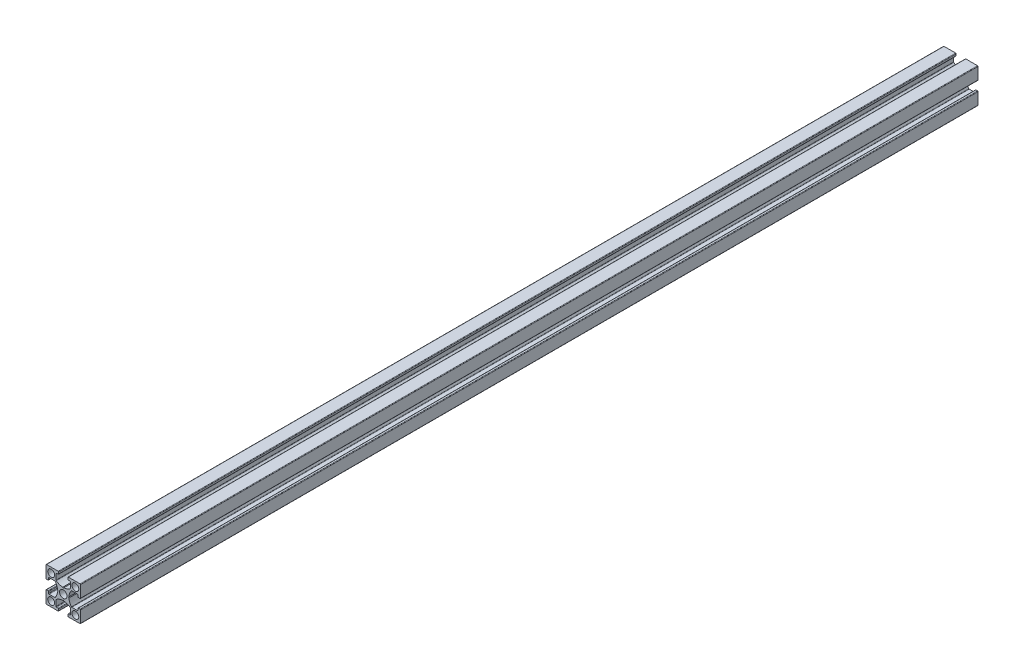
SolidWorks part; units mm, degrees
ref_plane "정면" through (0, 0, 0) normal (0, 0, 1) x (1, 0, 0)
ref_plane "윗면" through (0, 0, 0) normal (0, 1, 0) x (1, 0, 0)
ref_plane "우측면" through (0, 0, 0) normal (1, 0, 0) x (0, 0, -1)
sketch "Model" plane through (0, 0, 0) normal (0, 0, 1) x (1, 0, 0)
  line L0 (2292.4151, 1187.1915) -> (2314.8128, 1187.1915) construction
  line L1 (2307.7639, 1192.1343) -> (2307.7639, 1195.3915)
  line L2 (2307.4639, 1195.6915) -> (2306.5639, 1195.6915)
  line L3 (2306.2639, 1195.9915) -> (2306.2639, 1196.8915)
  line L4 (2306.5639, 1197.1915) -> (2313.3139, 1197.1915)
  line L5 (2313.6139, 1196.8915) -> (2313.6139, 1190.1415)
  line L6 (2313.3139, 1189.8415) -> (2312.4139, 1189.8415)
  line L7 (2312.1139, 1190.1415) -> (2312.1139, 1191.0415)
  line L8 (2311.8139, 1191.3415) -> (2308.5567, 1191.3415)
  line L9 (2306.9212, 1187.4988) -> (2306.6139, 1187.1915)
  line L10 (2306.6139, 1187.1915) -> (2306.9212, 1186.8843)
  line L11 (2308.5567, 1183.0415) -> (2311.8139, 1183.0415)
  line L12 (2312.1139, 1183.3415) -> (2312.1139, 1184.2415)
  line L13 (2312.4139, 1184.5415) -> (2313.3139, 1184.5415)
  line L14 (2313.6139, 1184.2415) -> (2313.6139, 1177.4915)
  line L15 (2313.3139, 1177.1915) -> (2306.5639, 1177.1915)
  line L16 (2306.2639, 1177.4915) -> (2306.2639, 1178.3915)
  line L17 (2306.5639, 1178.6915) -> (2307.4639, 1178.6915)
  line L18 (2307.7639, 1178.9915) -> (2307.7639, 1182.2488)
  line L19 (2303.9212, 1183.8843) -> (2303.6139, 1184.1915)
  line L20 (2303.6139, 1184.1915) -> (2303.3066, 1183.8843)
  line L21 (2299.4639, 1182.2488) -> (2299.4639, 1178.9915)
  line L22 (2299.7639, 1178.6915) -> (2300.6639, 1178.6915)
  line L23 (2300.9639, 1178.3915) -> (2300.9639, 1177.4915)
  line L24 (2300.6639, 1177.1915) -> (2293.9139, 1177.1915)
  line L25 (2293.6139, 1177.4915) -> (2293.6139, 1184.2415)
  line L26 (2293.9139, 1184.5415) -> (2294.8139, 1184.5415)
  line L27 (2295.1139, 1184.2415) -> (2295.1139, 1183.3415)
  line L28 (2295.4139, 1183.0415) -> (2298.6712, 1183.0415)
  line L29 (2300.3066, 1186.8843) -> (2300.6139, 1187.1915)
  line L30 (2300.6139, 1187.1915) -> (2300.3066, 1187.4988)
  line L31 (2298.6712, 1191.3415) -> (2295.4139, 1191.3415)
  line L32 (2295.1139, 1191.0415) -> (2295.1139, 1190.1415)
  line L33 (2294.8139, 1189.8415) -> (2293.9139, 1189.8415)
  line L34 (2293.6139, 1190.1415) -> (2293.6139, 1196.8915)
  line L35 (2293.9139, 1197.1915) -> (2300.6639, 1197.1915)
  line L36 (2300.9639, 1196.8915) -> (2300.9639, 1195.9915)
  line L37 (2300.6639, 1195.6915) -> (2299.7639, 1195.6915)
  line L38 (2299.4639, 1195.3915) -> (2299.4639, 1192.1343)
  line L39 (2303.3066, 1190.4988) -> (2303.6139, 1190.1915)
  line L40 (2303.6139, 1190.1915) -> (2303.9212, 1190.4988)
  line L41 (2294.1139, 1194.1915) -> (2299.1139, 1194.1915) construction
  line L42 (2296.6139, 1196.6915) -> (2296.6139, 1191.6915) construction
  line L43 (2294.1139, 1180.1915) -> (2299.1139, 1180.1915) construction
  line L44 (2296.6139, 1177.6915) -> (2296.6139, 1182.6915) construction
  line L45 (2303.6139, 1198.3904) -> (2303.6139, 1175.9927) construction
  line L46 (2313.1139, 1194.1915) -> (2308.1139, 1194.1915) construction
  line L47 (2310.6139, 1196.6915) -> (2310.6139, 1191.6915) construction
  line L48 (2310.6139, 1177.6915) -> (2310.6139, 1182.6915) construction
  line L49 (2313.1139, 1180.1915) -> (2308.1139, 1180.1915) construction
  circle A0 centre (2303.6139, 1187.1915) radius 2.15
  circle A1 centre (2296.6139, 1194.1915) radius 2
  circle A2 centre (2296.6139, 1180.1915) radius 2
  circle A3 centre (2310.6139, 1194.1915) radius 2
  circle A4 centre (2310.6139, 1180.1915) radius 2
  arc A5 (2307.7639, 1195.3915) -> (2307.4639, 1195.6915) centre (2307.4639, 1195.3915) ccw
  arc A6 (2306.2639, 1195.9915) -> (2306.5639, 1195.6915) centre (2306.5639, 1195.9915) ccw
  arc A7 (2306.5639, 1197.1915) -> (2306.2639, 1196.8915) centre (2306.5639, 1196.8915) ccw
  arc A8 (2313.6139, 1196.8915) -> (2313.3139, 1197.1915) centre (2313.3139, 1196.8915) ccw
  arc A9 (2313.3139, 1189.8415) -> (2313.6139, 1190.1415) centre (2313.3139, 1190.1415) ccw
  arc A10 (2312.1139, 1190.1415) -> (2312.4139, 1189.8415) centre (2312.4139, 1190.1415) ccw
  arc A11 (2312.1139, 1191.0415) -> (2311.8139, 1191.3415) centre (2311.8139, 1191.0415) ccw
  arc A12 (2308.5567, 1191.3415) -> (2308.3217, 1191.2281) centre (2308.5567, 1191.0415) ccw
  arc A13 (2308.3217, 1191.2281) -> (2306.9212, 1187.4988) centre (2313.4048, 1187.1915) ccw
  arc A14 (2306.9212, 1186.8843) -> (2308.3217, 1183.155) centre (2313.4048, 1187.1915) ccw
  arc A15 (2308.3217, 1183.155) -> (2308.5567, 1183.0415) centre (2308.5567, 1183.3415) ccw
  arc A16 (2311.8139, 1183.0415) -> (2312.1139, 1183.3415) centre (2311.8139, 1183.3415) ccw
  arc A17 (2312.4139, 1184.5415) -> (2312.1139, 1184.2415) centre (2312.4139, 1184.2415) ccw
  arc A18 (2313.6139, 1184.2415) -> (2313.3139, 1184.5415) centre (2313.3139, 1184.2415) ccw
  arc A19 (2313.3139, 1177.1915) -> (2313.6139, 1177.4915) centre (2313.3139, 1177.4915) ccw
  arc A20 (2306.2639, 1177.4915) -> (2306.5639, 1177.1915) centre (2306.5639, 1177.4915) ccw
  arc A21 (2306.5639, 1178.6915) -> (2306.2639, 1178.3915) centre (2306.5639, 1178.3915) ccw
  arc A22 (2307.4639, 1178.6915) -> (2307.7639, 1178.9915) centre (2307.4639, 1178.9915) ccw
  arc A23 (2307.7639, 1182.2488) -> (2307.6505, 1182.4837) centre (2307.4639, 1182.2488) ccw
  arc A24 (2307.6505, 1182.4837) -> (2303.9212, 1183.8843) centre (2303.6139, 1177.4007) ccw
  arc A25 (2303.3066, 1183.8843) -> (2299.5774, 1182.4837) centre (2303.6139, 1177.4007) ccw
  arc A26 (2299.5774, 1182.4837) -> (2299.4639, 1182.2488) centre (2299.7639, 1182.2488) ccw
  arc A27 (2299.4639, 1178.9915) -> (2299.7639, 1178.6915) centre (2299.7639, 1178.9915) ccw
  arc A28 (2300.9639, 1178.3915) -> (2300.6639, 1178.6915) centre (2300.6639, 1178.3915) ccw
  arc A29 (2300.6639, 1177.1915) -> (2300.9639, 1177.4915) centre (2300.6639, 1177.4915) ccw
  arc A30 (2293.6139, 1177.4915) -> (2293.9139, 1177.1915) centre (2293.9139, 1177.4915) ccw
  arc A31 (2293.9139, 1184.5415) -> (2293.6139, 1184.2415) centre (2293.9139, 1184.2415) ccw
  arc A32 (2295.1139, 1184.2415) -> (2294.8139, 1184.5415) centre (2294.8139, 1184.2415) ccw
  arc A33 (2295.1139, 1183.3415) -> (2295.4139, 1183.0415) centre (2295.4139, 1183.3415) ccw
  arc A34 (2298.6712, 1183.0415) -> (2298.9061, 1183.155) centre (2298.6712, 1183.3415) ccw
  arc A35 (2298.9061, 1183.155) -> (2300.3066, 1186.8843) centre (2293.8231, 1187.1915) ccw
  arc A36 (2300.3066, 1187.4988) -> (2298.9061, 1191.2281) centre (2293.8231, 1187.1915) ccw
  arc A37 (2298.9061, 1191.2281) -> (2298.6712, 1191.3415) centre (2298.6712, 1191.0415) ccw
  arc A38 (2295.4139, 1191.3415) -> (2295.1139, 1191.0415) centre (2295.4139, 1191.0415) ccw
  arc A39 (2294.8139, 1189.8415) -> (2295.1139, 1190.1415) centre (2294.8139, 1190.1415) ccw
  arc A40 (2293.6139, 1190.1415) -> (2293.9139, 1189.8415) centre (2293.9139, 1190.1415) ccw
  arc A41 (2293.9139, 1197.1915) -> (2293.6139, 1196.8915) centre (2293.9139, 1196.8915) ccw
  arc A42 (2300.9639, 1196.8915) -> (2300.6639, 1197.1915) centre (2300.6639, 1196.8915) ccw
  arc A43 (2300.6639, 1195.6915) -> (2300.9639, 1195.9915) centre (2300.6639, 1195.9915) ccw
  arc A44 (2299.7639, 1195.6915) -> (2299.4639, 1195.3915) centre (2299.7639, 1195.3915) ccw
  arc A45 (2299.4639, 1192.1343) -> (2299.5774, 1191.8994) centre (2299.7639, 1192.1343) ccw
  arc A46 (2299.5774, 1191.8994) -> (2303.3066, 1190.4988) centre (2303.6139, 1196.9824) ccw
  arc A47 (2303.9212, 1190.4988) -> (2307.6505, 1191.8994) centre (2303.6139, 1196.9824) ccw
  arc A48 (2307.6505, 1191.8994) -> (2307.7639, 1192.1343) centre (2307.4639, 1192.1343) ccw
extrude "보스-돌출1" add sketch "Model" along normal blind 520
